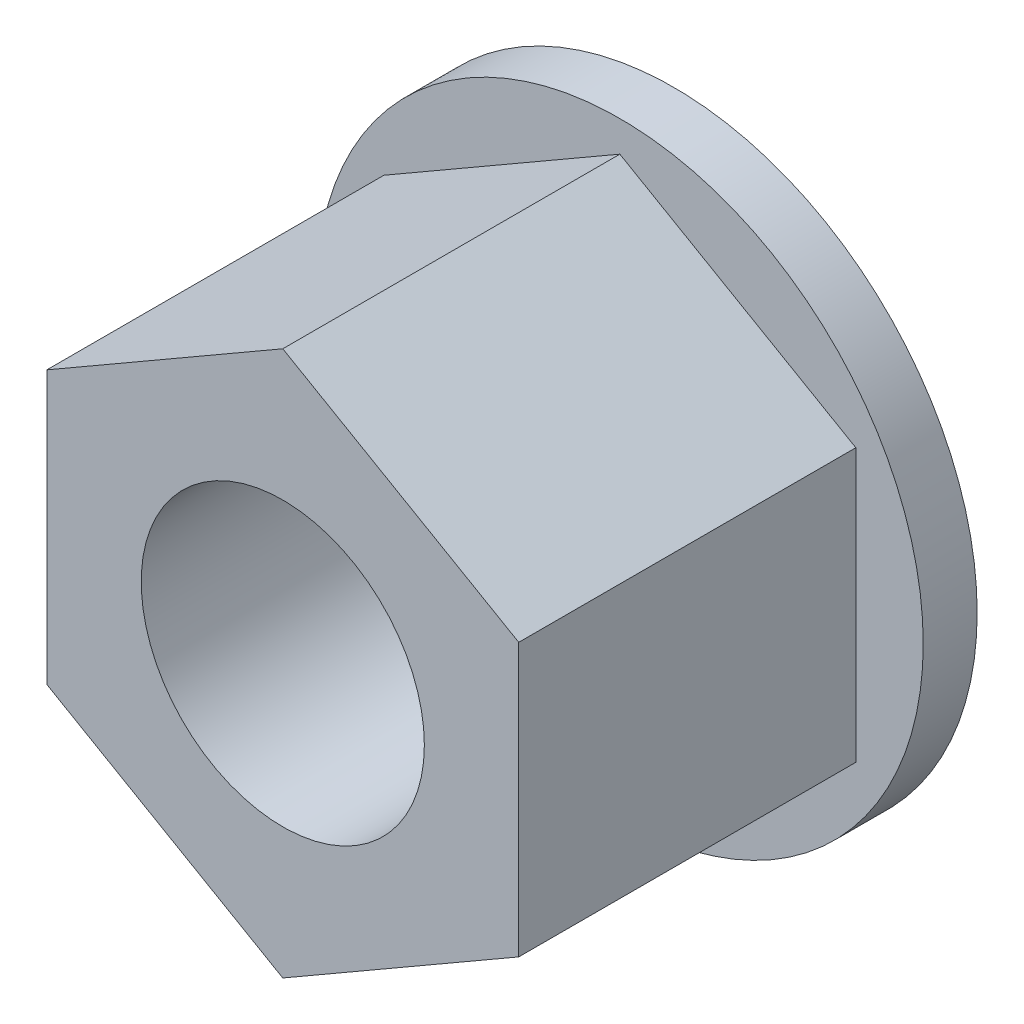
SolidWorks part; units mm, degrees
ref_plane "Front Plane" through (0, 0, 0) normal (0, 0, 1) x (1, 0, 0)
ref_plane "Top Plane" through (0, 0, 0) normal (0, 1, 0) x (1, 0, 0)
ref_plane "Right Plane" through (0, 0, 0) normal (1, 0, 0) x (0, 0, -1)
sketch "M4 washer envelope profile" plane through (0, 0, 0) normal (0, 0, 1) x (1, 0, 0)
  circle A0 centre (0, 0) radius 4.5
  circle A1 centre (0, 0) radius 2.1
extrude "M4 washer envelope" add sketch "M4 washer envelope profile" along normal blind 0.8
sketch "M4 locknut outer envelope profile" plane through (0, 0, 0) normal (0, 0, 1) x (1, 0, 0)
  line L0 (3.5, 2.0207) -> (0, 4.0415)
  line L1 (0, 4.0415) -> (-3.5, 2.0207)
  line L2 (-3.5, 2.0207) -> (-3.5, -2.0207)
  line L3 (-3.5, -2.0207) -> (0, -4.0415)
  line L4 (0, -4.0415) -> (3.5, -2.0207)
  line L5 (3.5, -2.0207) -> (3.5, 2.0207)
  circle A0 centre (0, 0) radius 2.1
extrude "M4 locknut outer envelope" add sketch "M4 locknut outer envelope profile" along normal blind 5 from offset 0.8
